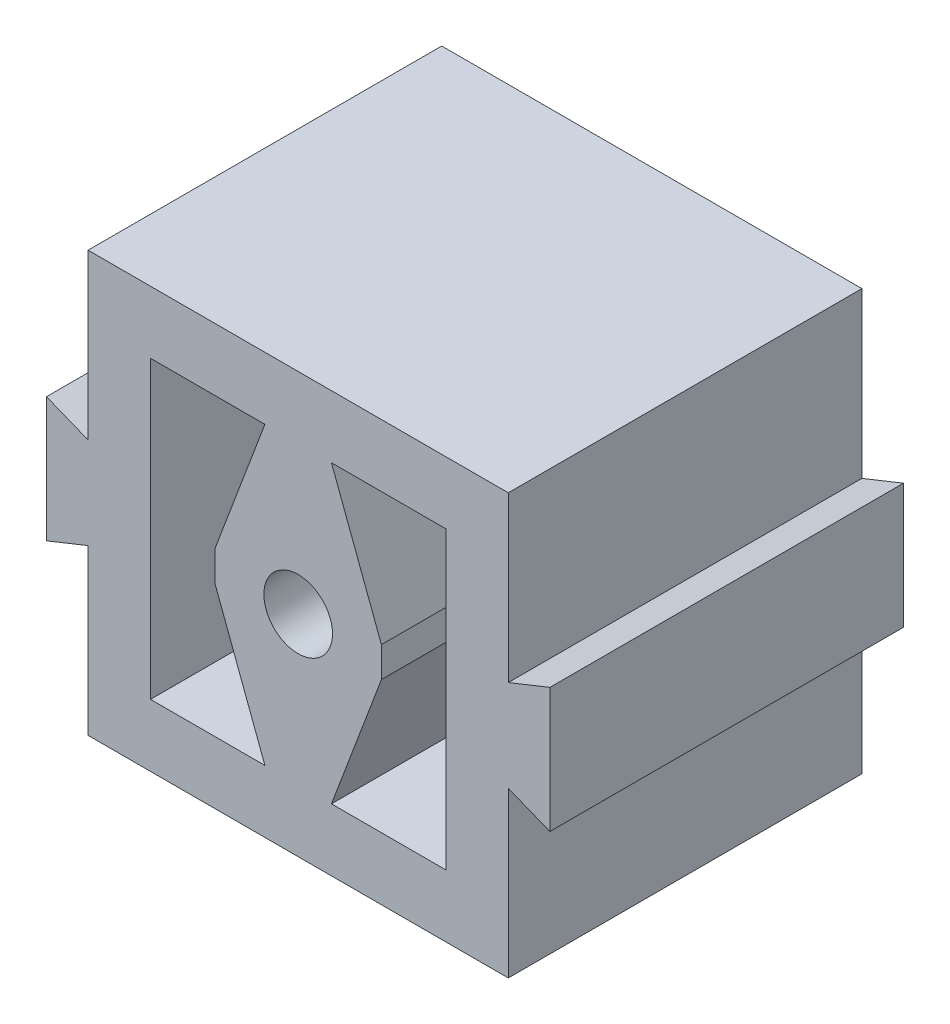
SolidWorks part; units mm, degrees
ref_plane "Front Plane" through (0, 0, 0) normal (0, 0, 1) x (1, 0, 0)
ref_plane "Top Plane" through (0, 0, 0) normal (0, 1, 0) x (1, 0, 0)
ref_plane "Right Plane" through (0, 0, 0) normal (1, 0, 0) x (0, 0, -1)
sketch "Sketch1" plane through (0, 0, 0) normal (0, 0, 1) x (1, 0, 0)
  line L0 (25.25, 5.5) -> (30.25, 7.5)
  line L1 (-25.25, 25.25) -> (25.25, 25.25)
  line L2 (-25.25, 25.25) -> (-25.25, -25.25)
  line L3 (-25.25, -25.25) -> (25.25, -25.25)
  line L4 (25.25, 25.25) -> (25.25, -25.25)
  line L5 (-25.25, 25.25) -> (25.25, -25.25) construction
  line L6 (-25.25, -25.25) -> (25.25, 25.25) construction
  line L7 (30.25, 7.5) -> (30.25, -7.5)
  line L8 (30.25, -7.5) -> (25.25, -5.5)
  line L9 (25.25, -5.5) -> (25.25, 5.5)
  line L10 (-25.25, 5.5) -> (-30.25, 7.5)
  line L11 (-30.25, 7.5) -> (-30.25, -7.5)
  line L12 (-30.25, -7.5) -> (-25.25, -5.5)
  line L13 (-25.25, -5.5) -> (-25.25, 5.5)
  line L14 (-25.25, 25.25) -> (-30.25, 7.5) construction
  line L15 (-30.25, -7.5) -> (-25.25, -25.25) construction
  line L16 (25.25, -25.25) -> (30.25, -7.5) construction
  line L17 (30.25, 7.5) -> (25.25, 25.25) construction
  point P0 (0, 0)
  dimension "D1" = 50.5
  dimension "D2" = 50.5
  dimension "D3" = 15
  dimension "D4" = 2
  dimension "D5" = 5
extrude "Boss-Extrude1" add sketch "Sketch1" along normal blind 42.5 contours L4 L1 L2 L3 | L11 L12 L2 L10 | L8 L7 L0 L4
sketch "Sketch2" plane through (0, 0, 42.5) normal (0, 0, 1) x (1, 0, 0)
  line L1 (-25.25, 25.25) -> (25.25, 25.25) construction
  line L2 (0, 25.25) -> (0, -25.25) construction
  line L3 (-25.25, -25.25) -> (25.25, -25.25) construction
  circle A0 centre (0, 0) radius 4.125
  dimension "D1" = 8.25
extrude "Cut-Extrude1" cut sketch "Sketch2" against normal blind 46.2
sketch "Sketch4" plane through (0, 0, 42.5) normal (0, 0, 1) x (1, 0, 0)
  line L0 (-17.75, -17.75) -> (-17.75, 17.75)
  line L1 (-17.75, 17.75) -> (-4, 17.75)
  line L2 (-4, 17.75) -> (-10, 1.8209)
  line L3 (-10, 1.8209) -> (-10, -1.8209)
  line L4 (-10, -1.8209) -> (-4, -17.75)
  line L5 (-4, -17.75) -> (-17.75, -17.75)
  line L6 (-25.25, 25.25) -> (25.25, 25.25) construction
  line L7 (-25.25, -25.25) -> (25.25, -25.25) construction
  line L8 (-25.25, -5.5) -> (-25.25, -25.25) construction
  line L9 (0, 25.25) -> (0, -25.25) construction
  line L10 (10, -1.8209) -> (4, -17.75)
  line L11 (10, 1.8209) -> (10, -1.8209)
  line L12 (4, 17.75) -> (10, 1.8209)
  line L13 (17.75, 17.75) -> (4, 17.75)
  line L14 (17.75, -17.75) -> (17.75, 17.75)
  line L15 (4, -17.75) -> (17.75, -17.75)
  circle A0 centre (0, 0) radius 4.125 construction
  dimension "D1" = 7.5
  dimension "D2" = 7.5
  dimension "D3" = 7.5
  dimension "D4" = 10
  dimension "D5" = 10
  dimension "D6" = 10
  dimension "D7" = 4
  dimension "D8" = 4
extrude "Cut-Extrude2" cut sketch "Sketch4" against normal blind 76
